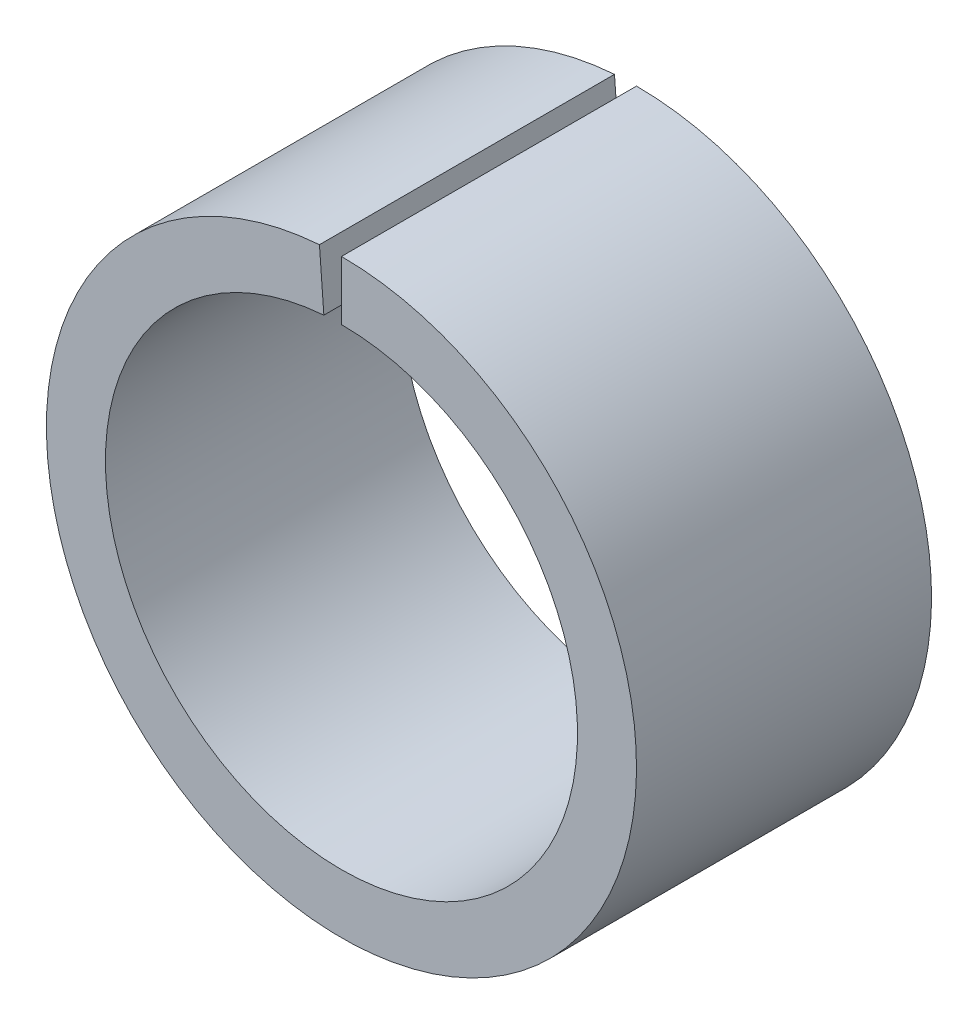
SolidWorks part; units mm, degrees
ref_plane "前视基准面" through (0, 0, 0) normal (0, 0, 1) x (1, 0, 0)
ref_plane "上视基准面" through (0, 0, 0) normal (0, 1, 0) x (1, 0, 0)
ref_plane "右视基准面" through (0, 0, 0) normal (1, 0, 0) x (0, 0, -1)
sketch "草图1" plane through (0, 0, 0) normal (0, 0, 1) x (1, 0, 0)
  circle A0 centre (0, 0) radius 5
  circle A1 centre (0, 0) radius 4
  dimension "D1" = 8
  dimension "D2" = 10
extrude "凸台-拉伸1" add sketch "草图1" along normal blind 5
sketch "草图2" plane through (0, 0, 5) normal (0, 0, 1) x (1, 0, 0)
  line L0 (0, 0) -> (0, 10.7779)
  line L1 (0, 10.7779) -> (-0.8065, 10.7779)
  line L2 (-0.8065, 10.7779) -> (0, 0)
extrude "切除-拉伸1" cut sketch "草图2" against normal blind 10
